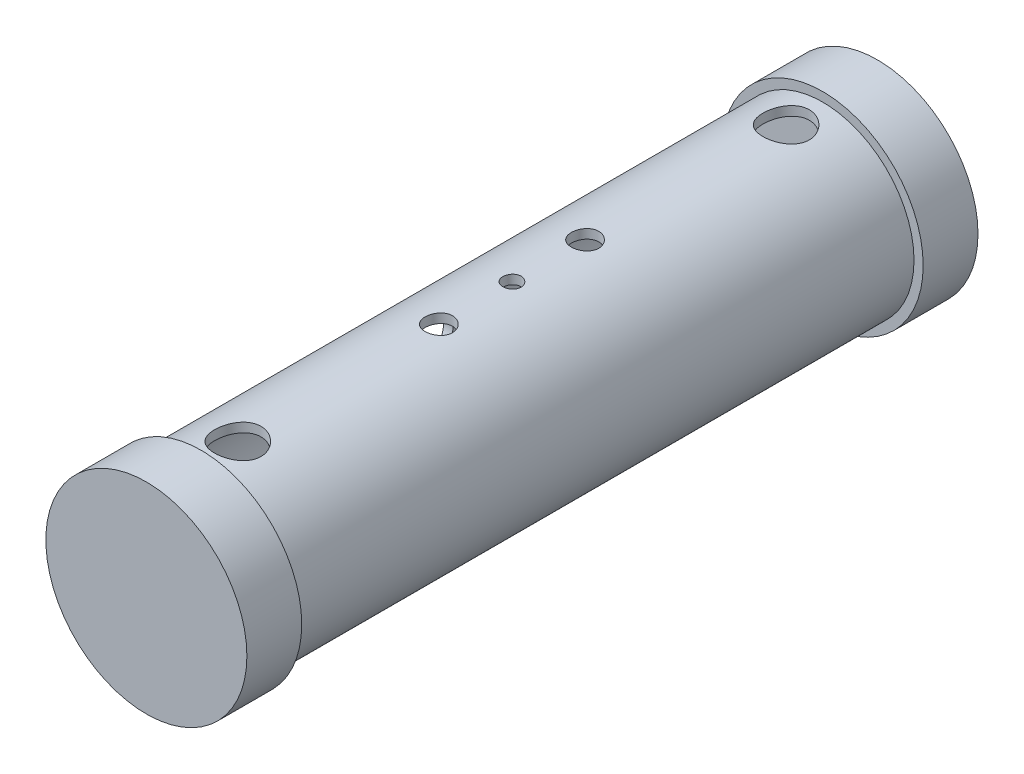
SolidWorks part; units mm, degrees
ref_plane "Alzado" through (0, 0, 0) normal (0, 0, 1) x (1, 0, 0)
ref_plane "Planta" through (0, 0, 0) normal (0, 1, 0) x (1, 0, 0)
ref_plane "Vista lateral" through (0, 0, 0) normal (1, 0, 0) x (0, 0, -1)
sketch "Croquis1" plane through (0, 0, 0) normal (0, 0, 1) x (1, 0, 0)
  circle A0 centre (0, 0) radius 50
  circle A1 centre (0, 0) radius 45
extrude "Saliente-Extruir1" add sketch "Croquis1" along normal blind 400
sketch "Croquis2" plane through (0, 0, 0) normal (0, 0, 1) x (1, 0, 0)
  circle A1 centre (0, 0) radius 55
extrude "Saliente-Extruir2" add sketch "Croquis2" along normal blind 30
ref_plane "Plano1" through (0, 0, 400) normal (0, 0, 1) x (1, 0, 0)
sketch "Croquis3" plane through (0, 0, 400) normal (0, 0, 1) x (1, 0, 0)
  circle A0 centre (0, 0) radius 55
extrude "Saliente-Extruir3" add sketch "Croquis3" against normal blind 30
sketch "Croquis4" plane through (0, 0, 0) normal (1, 0, 0) x (0, 0, -1)
  circle A0 centre (-200, 0) radius 12.75
extrude "Cortar-Extruir1" cut sketch "Croquis4" against normal blind 179
ref_plane "Plano2" through (0, 50, 0) normal (0, 1, 0) x (1, 0, 0)
sketch "Croquis5" plane through (0, 50, 0) normal (0, 1, 0) x (1, 0, 0)
  circle A0 centre (0, -240) radius 7.5
  circle A1 centre (0, -160) radius 7.5
  circle A2 centre (0, -200) radius 5
  circle A3 centre (0, -350) radius 12.7
  circle A4 centre (0, -50) radius 12.7
extrude "Cortar-Extruir2" cut sketch "Croquis5" against normal blind 60
